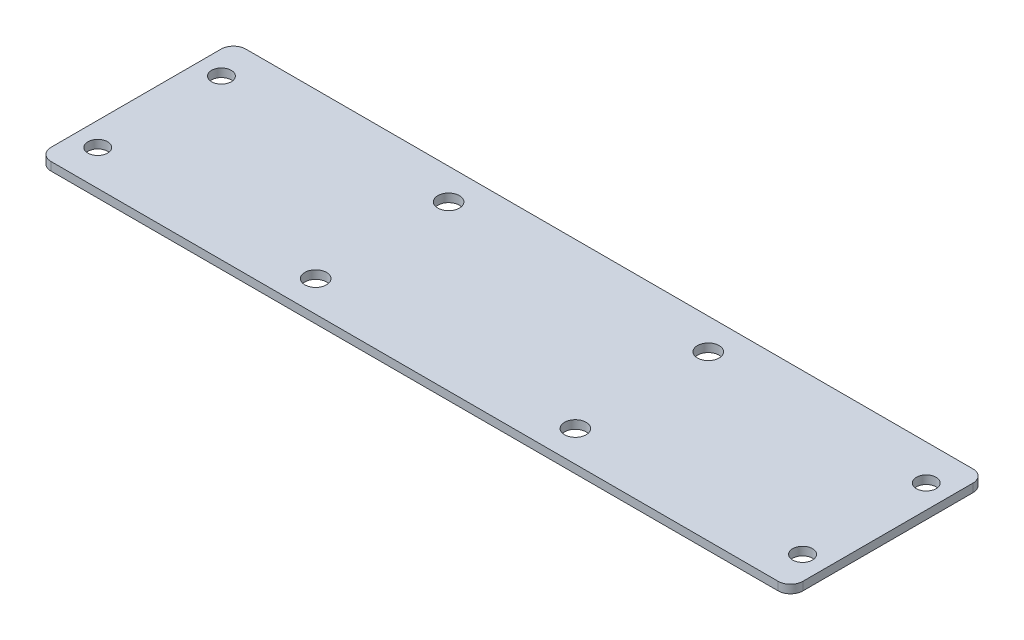
SolidWorks part; units mm, degrees
material "Acrylic (Medium-high impact)"
ref_plane "Front Plane" through (0, 0, 0) normal (0, 0, 1) x (1, 0, 0)
ref_plane "Top Plane" through (0, 0, 0) normal (0, 1, 0) x (1, 0, 0)
ref_plane "Right Plane" through (0, 0, 0) normal (1, 0, 0) x (0, 0, -1)
sketch "Sketch1" plane through (0, 0, 0) normal (0, 1, 0) x (1, 0, 0)
  line L0 (-60.8, -12.3481) -> (-60.8, -7.25) construction
  line L1 (-59.8, -6.25) -> (-53, -6.25) construction
  line L2 (-52, -7.25) -> (-52, -13.349) construction
  line L3 (-53, -14.35) -> (-58.8, -14.35) construction
  line L4 (-53, 6.25) -> (-59.8, 6.25) construction
  line L5 (-60.8, 7.25) -> (-60.8, 12.3481) construction
  line L6 (-58.8, 14.35) -> (-53, 14.35) construction
  line L7 (-52, 13.349) -> (-52, 7.25) construction
  line L8 (53, -6.25) -> (59.8, -6.25) construction
  line L9 (60.8, -7.25) -> (60.8, -12.3481) construction
  line L10 (58.8, -14.35) -> (53, -14.35) construction
  line L11 (52, -13.349) -> (52, -7.25) construction
  line L12 (60.8, 12.3481) -> (60.8, 7.25) construction
  line L13 (59.8, 6.25) -> (53, 6.25) construction
  line L14 (52, 7.25) -> (52, 13.349) construction
  line L15 (53, 14.35) -> (58.8, 14.35) construction
  line L16 (-60.8, -12.3481) -> (-60.8, -7.25)
  line L17 (-59.8, -6.25) -> (-53, -6.25)
  line L18 (-52, -7.25) -> (-52, -13.349)
  line L19 (-53, -14.35) -> (-58.8, -14.35)
  line L20 (-53, 6.25) -> (-59.8, 6.25)
  line L21 (-60.8, 7.25) -> (-60.8, 12.3481)
  line L22 (-58.8, 14.35) -> (-53, 14.35)
  line L23 (-52, 13.349) -> (-52, 7.25)
  line L24 (53, -6.25) -> (59.8, -6.25)
  line L25 (60.8, -7.25) -> (60.8, -12.3481)
  line L26 (58.8, -14.35) -> (53, -14.35)
  line L27 (52, -13.349) -> (52, -7.25)
  line L28 (60.8, 12.3481) -> (60.8, 7.25)
  line L29 (59.8, 6.25) -> (53, 6.25)
  line L30 (52, 7.25) -> (52, 13.349)
  line L31 (53, 14.35) -> (58.8, 14.35)
  line L32 (-60.8, 15.75) -> (60.8, 15.75)
  line L33 (104.5, 15.75) -> (-104.5, 15.75) construction
  line L34 (-60.8, -15.75) -> (60.8, -15.75)
  line L35 (-66.88, -15.75) -> (66.88, -15.75) construction
  arc A0 (-59.8, -6.25) -> (-60.8, -7.25) centre (-59.8, -7.25) ccw construction
  circle A1 centre (-57, 10) radius 1.6
  circle A2 centre (-57, 10) radius 1.6
  circle A3 centre (-57, -10) radius 1.6
  circle A4 centre (-57, -10) radius 1.6
  circle A5 centre (57, -10) radius 1.6
  circle A6 centre (57, -10) radius 1.6
  circle A7 centre (57, 10) radius 1.6
  circle A8 centre (57, 10) radius 1.6
  arc A9 (-52, -7.25) -> (-53, -6.25) centre (-53, -7.25) ccw construction
  arc A10 (-60.8, 7.25) -> (-59.8, 6.25) centre (-59.8, 7.25) ccw construction
  arc A11 (-53, 6.25) -> (-52, 7.25) centre (-53, 7.25) ccw construction
  arc A12 (60.8, -7.25) -> (59.8, -6.25) centre (59.8, -7.25) ccw construction
  arc A13 (53, -6.25) -> (52, -7.25) centre (53, -7.25) ccw construction
  arc A14 (59.8, 6.25) -> (60.8, 7.25) centre (59.8, 7.25) ccw construction
  arc A15 (52, 7.25) -> (53, 6.25) centre (53, 7.25) ccw construction
  arc A16 (-59.8, -6.25) -> (-60.8, -7.25) centre (-59.8, -7.25) ccw
  arc A17 (-52, -7.25) -> (-53, -6.25) centre (-53, -7.25) ccw
  arc A18 (-60.8, 7.25) -> (-59.8, 6.25) centre (-59.8, 7.25) ccw
  arc A19 (-53, 6.25) -> (-52, 7.25) centre (-53, 7.25) ccw
  arc A20 (60.8, -7.25) -> (59.8, -6.25) centre (59.8, -7.25) ccw
  arc A21 (53, -6.25) -> (52, -7.25) centre (53, -7.25) ccw
  arc A22 (59.8, 6.25) -> (60.8, 7.25) centre (59.8, 7.25) ccw
  arc A23 (52, 7.25) -> (53, 6.25) centre (53, 7.25) ccw
  ellipse E0 centre (-53, -13.349) end of major axis (-53, -14.35) minor radius 1 (-53, -14.35) -> (-52, -13.349) ccw construction
  ellipse E1 centre (-58.8, -12.3481) end of major axis (-58.8, -10.3461) minor radius 2 (-60.8, -12.3481) -> (-58.8, -14.35) ccw construction
  ellipse E2 centre (-58.8, 12.3481) end of major axis (-58.8, 14.35) minor radius 2 (-58.8, 14.35) -> (-60.8, 12.3481) ccw construction
  ellipse E3 centre (-53, 13.349) end of major axis (-53, 14.35) minor radius 1 (-52, 13.349) -> (-53, 14.35) ccw construction
  ellipse E4 centre (58.8, -12.3481) end of major axis (58.8, -14.35) minor radius 2 (58.8, -14.35) -> (60.8, -12.3481) ccw construction
  ellipse E5 centre (53, -13.349) end of major axis (53, -14.35) minor radius 1 (52, -13.349) -> (53, -14.35) ccw construction
  ellipse E6 centre (53, 13.349) end of major axis (53, 14.35) minor radius 1 (53, 14.35) -> (52, 13.349) ccw construction
  ellipse E7 centre (58.8, 12.3481) end of major axis (58.8, 10.3461) minor radius 2 (60.8, 12.3481) -> (58.8, 14.35) ccw construction
  ellipse E8 centre (-53, -13.349) end of major axis (-53, -14.35) minor radius 1 (-53, -14.35) -> (-52, -13.349) ccw
  ellipse E9 centre (-58.8, -12.3481) end of major axis (-58.8, -10.3461) minor radius 2 (-60.8, -12.3481) -> (-58.8, -14.35) ccw
  ellipse E10 centre (-58.8, 12.3481) end of major axis (-58.8, 14.35) minor radius 2 (-58.8, 14.35) -> (-60.8, 12.3481) ccw
  ellipse E11 centre (-53, 13.349) end of major axis (-53, 14.35) minor radius 1 (-52, 13.349) -> (-53, 14.35) ccw
  ellipse E12 centre (58.8, -12.3481) end of major axis (58.8, -14.35) minor radius 2 (58.8, -14.35) -> (60.8, -12.3481) ccw
  ellipse E13 centre (53, -13.349) end of major axis (53, -14.35) minor radius 1 (52, -13.349) -> (53, -14.35) ccw
  ellipse E14 centre (53, 13.349) end of major axis (53, 14.35) minor radius 1 (53, 14.35) -> (52, 13.349) ccw
  ellipse E15 centre (58.8, 12.3481) end of major axis (58.8, 10.3461) minor radius 2 (60.8, 12.3481) -> (58.8, 14.35) ccw
  dimension "D1" = 0
  dimension "D2" = 0
  dimension "D3" = 0
  dimension "D4" = 0
sketch "Sketch2" plane through (0, 0, 0) normal (0, 1, 0) x (1, 0, 0)
  line L1 (-60.8, -15.75) -> (60.8, -15.75)
  line L2 (-60.8, -15.75) -> (-60.8, 15.75)
  line L3 (-60.8, 15.75) -> (60.8, 15.75)
  line L4 (60.8, -15.75) -> (60.8, 15.75)
  circle A0 centre (-57, 10) radius 1.6
  circle A1 centre (-57, -10) radius 1.6
  circle A2 centre (57, 10) radius 1.6
  circle A3 centre (57, -10) radius 1.6
  dimension "D1" = 3.2
extrude "Boss-Extrude1" add sketch "Sketch2" against normal blind 1.35
fillet "Fillet1" radius 2 4 edges at (-60.8, -0.675, -15.75) (60.8, -0.675, -15.75) (60.8, -0.675, 15.75) (-60.8, -0.675, 15.75)
sketch "Sketch3" plane through (0, 0, 0) normal (0, 1, 0) x (1, 0, 0)
  circle A1 centre (-21, -10.75) radius 1.75
  circle A2 centre (-21, -10.75) radius 1.75
  circle A3 centre (21, -10.75) radius 1.75
  circle A4 centre (21, -10.75) radius 1.75
  circle A5 centre (21, 10.75) radius 1.75
  circle A6 centre (21, 10.75) radius 1.75
  circle A7 centre (-21, 10.75) radius 1.75
  circle A8 centre (-21, 10.75) radius 1.75
  dimension "D1" = 0
  dimension "D2" = 0
  dimension "D3" = 0
  dimension "D4" = 0
extrude "Cut-Extrude1" cut sketch "Sketch3" against normal through all
equation "\"Black_acrylic\"= 1.35mm"
